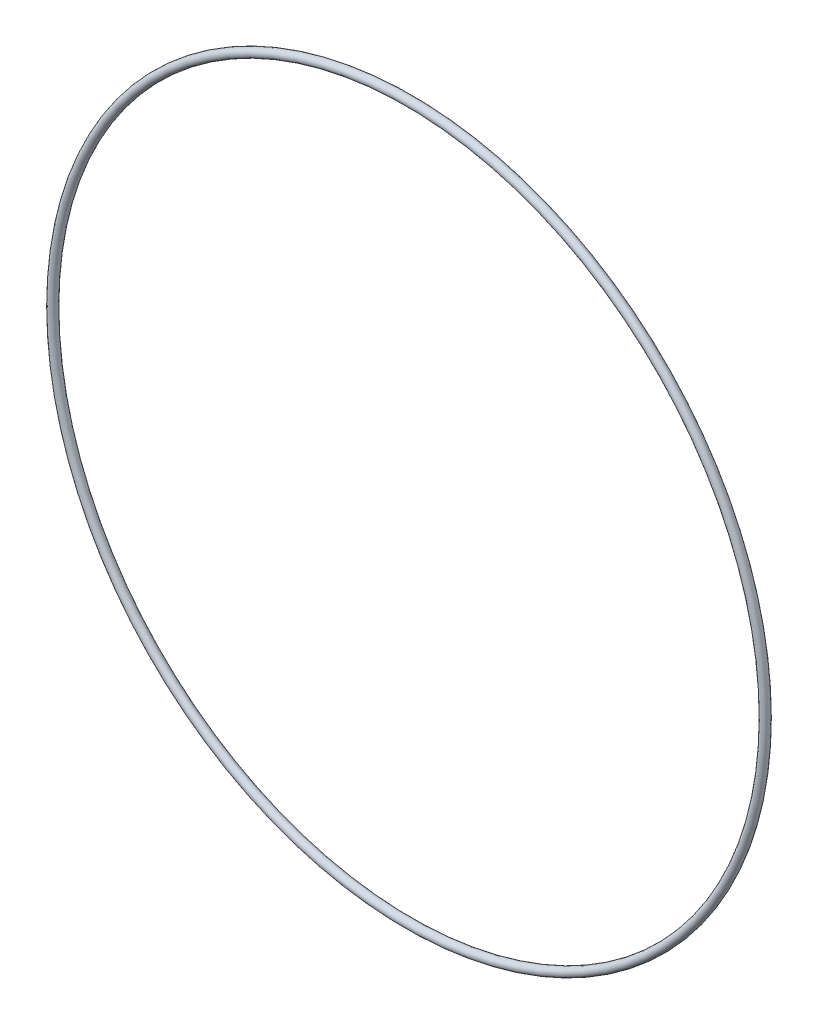
SolidWorks part; units mm, degrees
material "Nitrile Rubber"
ref_plane "Front Plane" through (0, 0, 0) normal (0, 0, 1) x (1, 0, 0)
ref_plane "Top Plane" through (0, 0, 0) normal (0, 1, 0) x (1, 0, 0)
ref_plane "Right Plane" through (0, 0, 0) normal (1, 0, 0) x (0, 0, -1)
sketch "Sketch1" plane through (0, 0, 0) normal (0, 0, 1) x (1, 0, 0)
  line L0 (0, 0) -> (0, 103.3655) construction
  line L1 (0, 0) -> (31.9225, 0) construction
  line L2 (0, 84) -> (87.2148, 80.5114)
  line L3 (106.4037, 61.2119) -> (108.5, 0)
  line L4 (108.5, 0) -> (106.3585, -70.2427)
  line L5 (102.8623, -80.9438) -> (63.028, -139.0356)
  line L6 (47.5, -147.7016) -> (0, -150)
  line L7 (-47.5, -147.7016) -> (0, -150)
  line L8 (-102.8623, -80.9438) -> (-63.028, -139.0356)
  line L9 (-108.5, 0) -> (-106.3585, -70.2427)
  line L10 (-106.4037, 61.2119) -> (-108.5, 0)
  line L11 (0, 84) -> (-87.2148, 80.5114)
  arc A0 (87.2148, 80.5114) -> (106.4037, 61.2119) centre (86.4154, 60.5274) cw
  arc A1 (106.3585, -70.2427) -> (102.8623, -80.9438) centre (86.3677, -69.6332) cw
  arc A2 (63.028, -139.0356) -> (47.5, -147.7016) centre (46.5334, -127.725) cw
  arc A3 (-63.028, -139.0356) -> (-47.5, -147.7016) centre (-46.5334, -127.725) ccw
  arc A4 (-106.3585, -70.2427) -> (-102.8623, -80.9438) centre (-86.3677, -69.6332) ccw
  arc A5 (-87.2148, 80.5114) -> (-106.4037, 61.2119) centre (-86.4154, 60.5274) ccw
  dimension "D2" = 20
  dimension "D5" = 20
  dimension "D6" = 20
  dimension "D1" = 84
  dimension "D3" = 217
  dimension "D4" = 150
  dimension "D7" = 95
  dimension "D8" = 175.419
  dimension "D9" = 174.4296
  dimension "D11" = 3.493
  dimension "D12" = 68.878
  dimension "D13" = 174.46
ref_axis "Axis1" through (0, 0, -8.5138) along (0, 0, 1)
sketch "Sketch6" plane through (0, 0, 0) normal (1, 0, 0) x (0, 0, -1)
  line L0 (8.5138, 0) -> (-3.3339, 0) construction
  circle A0 centre (0, 124) radius 1.5
  dimension "D1" = 3
  dimension "D2" = 245
revolve "Revolve1" add sketch "Sketch6" angle 360 about axis through (0, 0, -8.5138) along (0, 0, 1)
sketch "Sketch2" plane through (0, 0, 0) normal (0, 1, 0) x (1, 0, 0)
  circle A0 centre (-108.5, 0) radius 1.5
  dimension "D1" = 3
sweep "Sweep1" [suppressed] add profiles "Sketch2" path "Sketch1"
sketch "Sketch3" plane through (0, 0, 0) normal (0, 0, 1) x (1, 0, 0)
  line L0 (83, 80.3) -> (-83, 80.3)
  line L1 (-103.15, 60.15) -> (-103.15, -76.6)
  line L2 (-59.4193, -135.6794) -> (-42.9693, -140.7031)
  line L3 (42.9693, -140.7031) -> (59.4193, -135.6794)
  line L4 (103.15, -76.6) -> (103.15, 60.15)
  line L5 (0, 0) -> (134.5187, 0) construction
  line L6 (0, 0) -> (0, 55.15) construction
  arc A0 (103.15, 60.15) -> (83, 80.3) centre (83, 60.15) ccw
  arc A1 (-83, 80.3) -> (-103.15, 60.15) centre (-83, 60.15) ccw
  arc A2 (-103.15, -76.6) -> (-59.4193, -135.6794) centre (-41.377, -76.6) ccw
  arc A3 (-42.9693, -140.7031) -> (42.9693, -140.7031) centre (0, 0) ccw
  arc A4 (59.4193, -135.6794) -> (103.15, -76.6) centre (41.377, -76.6) ccw
  dimension "D2" = 227.418
  dimension "D4" = 20.15
  dimension "D5" = 61.773
  dimension "D6" = 76.6
  dimension "D1" = 80.3
  dimension "D3" = 206.3
sketch "Sketch4" plane through (0, 0, 0) normal (1, 0, 0) x (0, 0, -1)
  circle A0 centre (0, 80.3) radius 1.5
  dimension "D1" = 3
sweep "Sweep2" [suppressed] add profiles "Sketch4" path "Sketch3"
sketch "Sketch8" plane through (0, 0, 0) normal (1, 0, 0) x (0, 0, -1)
  line L0 (0, 101.2) -> (0, -101.2) construction
  circle A0 centre (0, 101.2) radius 1.5
  dimension "D1" = 3
sketch "Sketch7" plane through (0, 0, 0) normal (0, 0, 1) x (1, 0, 0)
  ellipse E0 centre (0, 0) end of major axis (-149, 0) minor radius 101.2
  dimension "D1" = 101.2
  dimension "D2" = 149
sweep "Sweep3" [suppressed] add profiles "Sketch8" path "Sketch7"
